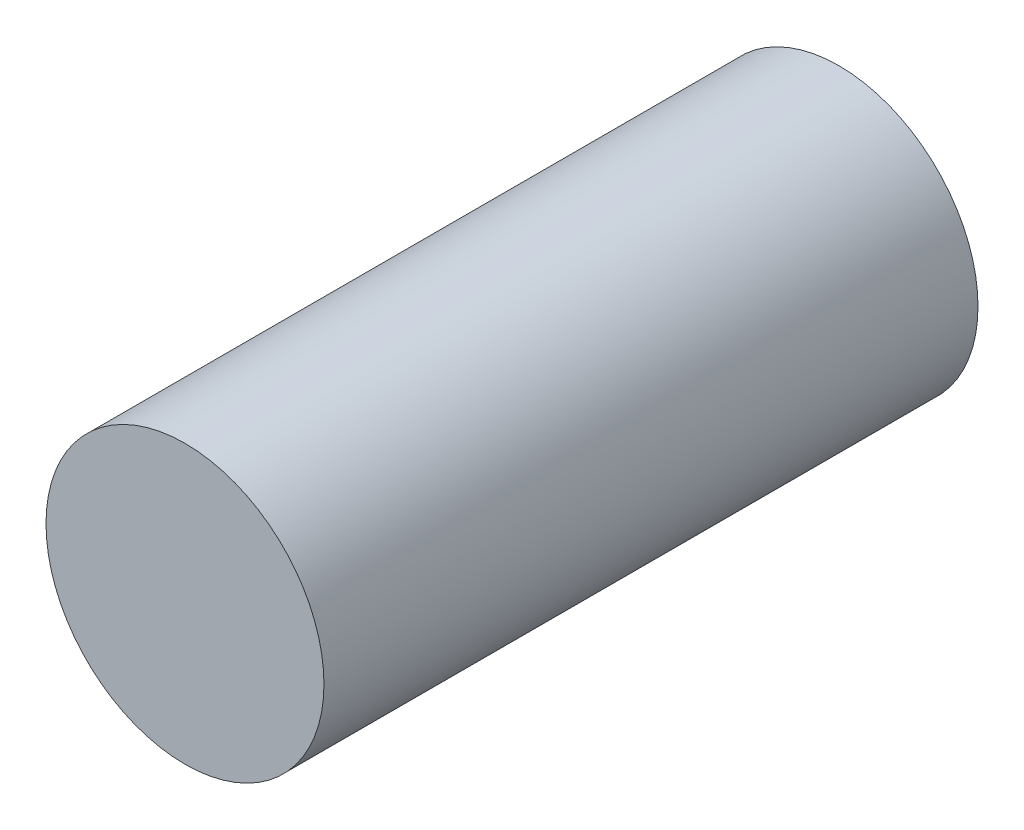
SolidWorks part; units mm, degrees
ref_plane "前视基准面" through (0, 0, 0) normal (0, 0, 1) x (1, 0, 0)
ref_plane "上视基准面" through (0, 0, 0) normal (0, 1, 0) x (1, 0, 0)
ref_plane "右视基准面" through (0, 0, 0) normal (1, 0, 0) x (0, 0, -1)
other "Configuration Table"
sketch "草图1" plane through (0, 0, 0) normal (0, 0, 1) x (1, 0, 0)
  circle A0 centre (0, 0) radius 8
extrude "凸台-拉伸1" add sketch "草图1" along normal blind 24
sketch "草图2" plane through (0, 0, 0) normal (0, 0, 1) x (1, 0, 0)
  circle A0 centre (0, 0) radius 42
extrude "凸台-拉伸2" add sketch "草图2" along normal blind 18
sketch "草图3" plane through (0, 0, 18) normal (0, 0, 1) x (1, 0, 0)
  line L0 (37.3016, 3.8521) -> (37.3889, 3.8612)
  line L1 (37.3016, 2.0353) -> (37.3016, 2.0305)
  arc A0 (41.5984, 5.7942) -> (41.9927, 0.7845) centre (0, 0) cw
  arc A1 (37.3016, 2.0305) -> (37.1592, 3.8374) centre (0, 0) ccw
sketch "草图4" plane through (0, 0, 24) normal (0, 0, 1) x (1, 0, 0)
  circle A0 centre (0, 0) radius 5.1
extrude "切除-拉伸2" cut sketch "草图4" against normal through all flip side to cut
